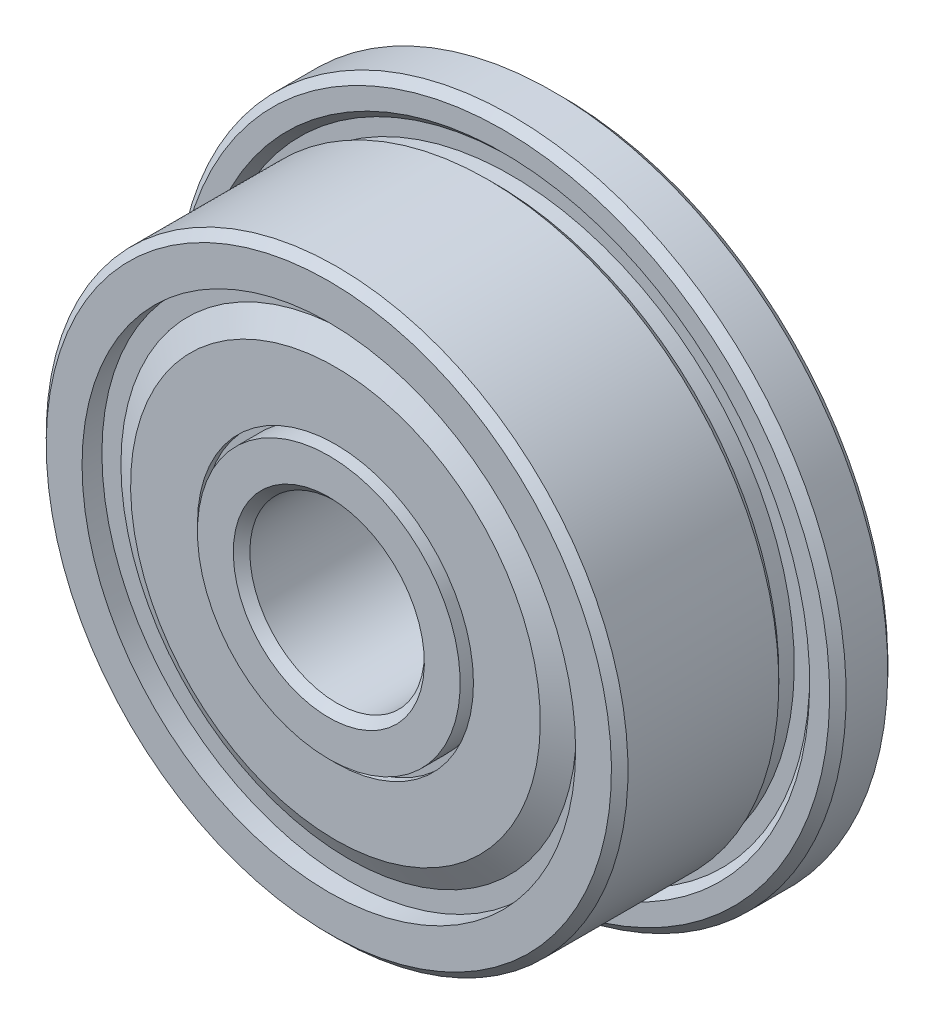
SolidWorks part; units mm, degrees
ref_plane "Front Plane" through (0, 0, 0) normal (0, 0, 1) x (1, 0, 0)
ref_plane "Top Plane" through (0, 0, 0) normal (0, 1, 0) x (1, 0, 0)
ref_plane "Right Plane" through (0, 0, 0) normal (1, 0, 0) x (0, 0, -1)
sketch "Sketch1" plane through (0, 0, 0) normal (1, 0, 0) x (0, 0, -1)
  line L0 (0, 5) -> (0, -5) construction
  line L1 (-2, 5) -> (2, 5) construction
  line L2 (0, 0) -> (2, 0) construction
  line L3 (2, 5.75) -> (2, -5.75) construction
  line L4 (2, -5.75) -> (1, -5.75) construction
  line L5 (2, 1.5) -> (0, 1.5) construction
  line L6 (2, 1.5) -> (2, -1.5) construction
  dimension "OD" = 10
  dimension "Width" = 4
  dimension "Flange Thickness" = 1
  dimension "ID" = 3
  dimension "Flange OD" = 11.5
sketch "Sketch2" plane through (0, 0, 0) normal (1, 0, 0) x (0, 0, -1)
  line L0 (2, 5.75) -> (1, 5.75)
  line L1 (1, 5.75) -> (1, 5.2652)
  line L2 (0.7348, 5) -> (-2, 5)
  line L3 (-2, 5) -> (-2, 3.8625)
  line L4 (-2, 3.8625) -> (-0.5053, 3.8625)
  line L5 (2, 5.75) -> (2, -5.75) construction
  line L6 (2, 3.8625) -> (2, 5.75)
  line L7 (2, 1.5) -> (-2, 1.5)
  line L8 (-2, 1.5) -> (-2, 2.6375)
  line L9 (-2, 2.6375) -> (-0.5053, 2.6375)
  line L10 (2, 2.6375) -> (2, 1.5)
  line L11 (0, 5) -> (0, 1.5) construction
  line L12 (-0.794, 3.25) -> (0.794, 3.25) construction
  line L13 (0.5053, 3.8625) -> (2, 3.8625)
  line L14 (0.5053, 2.6375) -> (2, 2.6375)
  line L15 (1, 5.2652) -> (1.1326, 5.1326)
  line L16 (1.1326, 5.1326) -> (1.1326, 4.8674)
  line L17 (1.1326, 4.8674) -> (0.8674, 4.8674)
  line L18 (0.8674, 4.8674) -> (0.7348, 5)
  line L19 (1, 5) -> (1.1326, 4.8674) construction
  line L20 (1.1326, 5.1326) -> (0.8674, 4.8674) construction
  line L21 (0.7348, 5) -> (1, 5) construction
  line L22 (1, 5) -> (1, 5.2652) construction
  line L23 (-2, 0) -> (2, 0) construction
  circle A0 centre (0, 3.25) radius 0.794 construction
  arc A1 (-0.5053, 3.8625) -> (0.5053, 3.8625) centre (0, 3.25) cw
  arc A2 (-0.5053, 2.6375) -> (0.5053, 2.6375) centre (0, 3.25) ccw
  dimension "Ball Dia." = 1.588
  dimension "D2" = 135
  dimension "D3" = 0.375
  dimension "Race Thikness" = 1.1375
  dimension "D4" = 1.225
revolve "Revolve1" add sketch "Sketch2" angle 360 about L2
fillet "Fillet1" radius 0.1422 3 edges at (0, -5.75, -2) (0, -5.75, -1) (0, -5, 2) profile chamfer
sketch "Sketch3" plane through (0, 0, 0) normal (0, 0, 1) x (1, 0, 0)
  line L0 (-1.5, 0) -> (1.5, 0) construction
  line L1 (-5, 0) -> (5, 0) construction
  point P5 (0, 0)
  dimension "ID2" = 3
  dimension "OD2" = 10
fillet "Fillet2" radius 0.1422 2 edges at (0, -1.5, -2) (0, -1.5, 2) profile chamfer
sketch "Sketch7" plane through (0, 0, 0) normal (0, 0, 1) x (1, 0, 0)
  line L0 (0, 4.044) -> (0, 2.456)
  line L1 (0, 5.75) -> (0, -5.75) construction
  line L2 (-1.0189, 4.044) -> (0, 0) construction
  line L3 (0, 0) -> (1.0189, 4.044) construction
  line L4 (1.0189, 4.044) -> (-1.0189, 4.044) construction
  circle A0 centre (0, 3.25) radius 0.794 construction
  circle A1 centre (0, 0) radius 4.044 construction
  circle A2 centre (0, 0) radius 2.456 construction
  arc A4 (0, 4.044) -> (0, 2.456) centre (0, 3.25) ccw
  dimension "D1" = 28.282
revolve "Revolve3" add sketch "Sketch7" angle 360 about L0
pattern_circular "CirPattern3" count 9 over 360 about axis through (0, 0, 0) along (0, 0, 1) of bodies 107
sketch "Sketch8" plane through (0, 0, 0) normal (1, 0, 0) x (0, 0, -1)
  line L1 (-2, 3.8625) -> (-1.545, 3.8625)
  line L2 (-2, 3.8625) -> (-2, 4.2417)
  line L3 (-2, 4.2417) -> (-1.545, 4.2417)
  line L4 (-1.545, 3.8625) -> (-1.545, 4.2417)
  line L5 (2, 3.8625) -> (1.545, 3.8625)
  line L6 (2, 3.8625) -> (2, 4.2417)
  line L7 (2, 4.2417) -> (1.545, 4.2417)
  line L8 (1.545, 3.8625) -> (1.545, 4.2417)
  line L9 (2, 2.6375) -> (1.545, 2.6375)
  line L10 (2, 2.6375) -> (2, 2.2583)
  line L11 (2, 2.2583) -> (1.545, 2.2583)
  line L12 (1.545, 2.6375) -> (1.545, 2.2583)
  line L13 (-2, 2.6375) -> (-1.545, 2.6375)
  line L14 (-2, 2.6375) -> (-2, 2.2583)
  line L15 (-2, 2.2583) -> (-1.545, 2.2583)
  line L16 (-1.545, 2.6375) -> (-1.545, 2.2583)
  dimension "D1" = 0.3792
  dimension "D2" = 0.455
revolve "Cut-Revolve1" cut sketch "Sketch8" angle 360 about L2
sketch "Sketch9" plane through (0, 0, 0) normal (1, 0, 0) x (0, 0, -1)
  line L0 (-1.545, 4.2417) -> (-1.545, 3.8845)
  line L1 (-1.545, 3.8845) -> (-1.7725, 3.4905)
  line L2 (-1.7725, 3.4905) -> (-1.7725, 2.3721)
  line L3 (1.7725, 2.3721) -> (1.7725, 2.2583) construction
  line L4 (1.545, 4.2417) -> (1.545, 3.8845)
  line L5 (1.545, 3.8845) -> (1.7725, 3.4905)
  line L6 (1.7725, 3.4905) -> (1.7725, 2.3721)
  line L7 (2, 2.2583) -> (1.545, 2.2583) construction
  line L8 (-1.6588, 4.2417) -> (-1.6588, 3.915)
  line L9 (-1.6588, 3.915) -> (-1.8863, 3.521)
  line L10 (-1.8863, 3.521) -> (-1.8863, 2.3721)
  line L11 (-1.545, 4.2417) -> (-1.6588, 4.2417)
  line L12 (-1.7725, 2.3721) -> (-1.8863, 2.3721)
  line L13 (1.6588, 4.2417) -> (1.6588, 3.915)
  line L14 (1.6588, 3.915) -> (1.8863, 3.521)
  line L15 (1.8863, 3.521) -> (1.8863, 2.3721)
  line L16 (1.545, 4.2417) -> (1.6588, 4.2417)
  line L17 (1.7725, 2.3721) -> (1.8863, 2.3721)
  line L18 (-1.545, 3.8845) -> (-1.545, 2.5308) construction
  line L19 (1.545, 3.8845) -> (1.545, 4.2417) construction
  line L20 (-1.545, 2.2583) -> (-2, 2.2583) construction
  line L22 (-1.7725, 2.3721) -> (-1.7725, 2.2583) construction
  dimension "D2" = 150
  dimension "D1" = 150
  dimension "D5" = 0.455
  dimension "D3" = 0.1138
  dimension "D4" = 0.1138
  dimension "D6" = 0.3571
revolve "Revolve4" add sketch "Sketch9" angle 360 about L2
equation "\"D1@Fillet1\"=\"Race Thikness@Sketch2\"/8"
equation "\"ID2@Sketch3\" = \"ID@Sketch1\""
equation "\"OD2@Sketch3\" = \"OD@Sketch1\""
equation "\"D1@Fillet2\"=\"Race Thikness@Sketch2\"/8"
equation "\"D1@CirPattern3\"=360/\"D1@Sketch7\"-4"
equation "\"D1@Sketch8\"=\"Race Thikness@Sketch2\"/3"
equation "\"D2@Sketch8\"=\"Race Thikness@Sketch2\"/2.5"
equation "\"D3@Sketch9\"=\"D5@Sketch9\"/4"
equation "\"D4@Sketch9\"=\"D5@Sketch9\"/4"
equation "\"D1@Sketch9\"=\"D2@Sketch9\""
equation "\"Ball Dia.@Sketch2\" = \"D1@Sketch2\"*.5"
equation "\"D4@Sketch2\"=((\"OD@Sketch1\"-\"ID@Sketch1\")/2)*.35"
